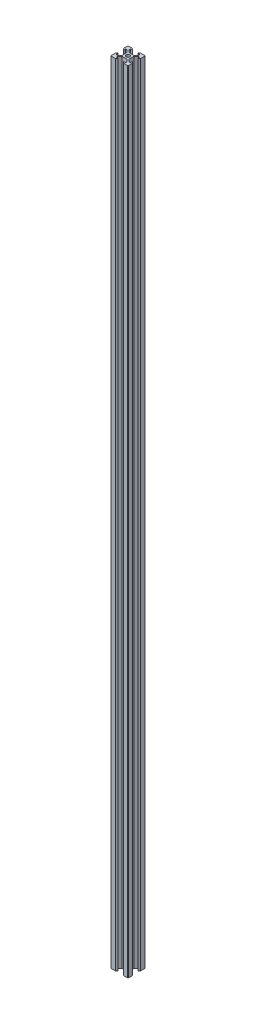
SolidWorks part; units mm, degrees
ref_plane "Front Plane" through (0, 0, 0) normal (0, 0, 1) x (1, 0, 0)
ref_plane "Top Plane" through (0, 0, 0) normal (0, 1, 0) x (1, 0, 0)
ref_plane "Right Plane" through (0, 0, 0) normal (1, 0, 0) x (0, 0, -1)
sketch "Sketch1" plane through (0, 0, 0) normal (1, 0, 0) x (0, 0, -1)
  line L0 (0, 0) -> (0, 914.4)
  dimension "D1" = 914.4
other "Vslot2020 2020(5)"
ref_plane "Plane5" through (0, 0, 0) normal (0, 1, 0) x (0, 0, 1)
sketch "Sketch2" plane through (0, 0, 0) normal (0, 1, 0) x (0, 0, 1)
  line L58 (13.9, 7.1491) -> (13.9, 12.8445)
  line L59 (13.9, 12.8445) -> (16.5585, 15.4922)
  line L60 (16.5585, 15.4922) -> (16.5507, 15.5)
  line L61 (16.5507, 15.5) -> (18.2, 15.5)
  line L62 (18.2, 15.5) -> (18.2, 13.12)
  line L63 (18.2, 13.12) -> (18.5344, 13.12)
  line L64 (18.5344, 13.12) -> (20, 14.58)
  line L65 (20, 14.58) -> (20, 19.5)
  line L66 (19.5, 20) -> (14.575, 20)
  line L67 (14.575, 20) -> (13.12, 18.545)
  line L68 (13.12, 18.545) -> (13.12, 18.2)
  line L69 (13.12, 18.2) -> (15.5, 18.2)
  line L70 (15.5, 18.2) -> (15.5, 16.555)
  line L71 (15.5, 16.555) -> (12.8341, 13.9)
  line L72 (12.8341, 13.9) -> (7.155, 13.9)
  line L73 (7.155, 13.9) -> (4.5, 16.555)
  line L74 (4.5, 16.555) -> (4.5, 18.2)
  line L75 (4.5, 18.2) -> (6.875, 18.2)
  line L76 (6.875, 18.2) -> (6.875, 18.545)
  line L77 (6.875, 18.545) -> (5.42, 20)
  line L78 (5.42, 20) -> (0.5, 20)
  line L79 (0, 19.5) -> (0, 14.58)
  line L80 (0, 14.58) -> (1.46, 13.12)
  line L81 (1.46, 13.12) -> (1.8, 13.12)
  line L82 (1.8, 13.12) -> (1.8, 15.5)
  line L83 (1.8, 15.5) -> (3.445, 15.5)
  line L84 (3.445, 15.5) -> (3.4393, 15.4943)
  line L85 (3.4393, 15.4943) -> (6.0943, 12.8393)
  line L86 (6.0943, 12.8393) -> (6.1, 12.845)
  line L87 (6.1, 12.845) -> (6.1, 7.1491)
  line L88 (6.1, 7.1491) -> (3.4393, 4.5)
  line L89 (3.4393, 4.5) -> (1.8, 4.5)
  line L90 (1.8, 4.5) -> (1.8, 6.88)
  line L91 (1.8, 6.88) -> (1.46, 6.88)
  line L92 (1.46, 6.88) -> (0, 5.42)
  line L93 (0, 5.42) -> (0, 0.5)
  line L94 (0.5, 0) -> (5.42, 0)
  line L95 (5.42, 0) -> (6.875, 1.455)
  line L96 (6.875, 1.455) -> (6.875, 1.8)
  line L97 (6.875, 1.8) -> (4.5, 1.8)
  line L98 (4.5, 1.8) -> (4.5, 3.4393)
  line L99 (4.5, 3.4393) -> (7.1583, 6.0861)
  line L100 (7.1583, 6.0861) -> (7.1445, 6.1)
  line L101 (7.1445, 6.1) -> (12.8546, 6.1)
  line L102 (12.8546, 6.1) -> (12.8412, 6.0865)
  line L103 (12.8412, 6.0865) -> (15.4997, 3.4375)
  line L104 (15.4997, 3.4375) -> (15.5, 3.4377)
  line L105 (15.5, 3.4377) -> (15.5, 1.8)
  line L106 (15.5, 1.8) -> (13.12, 1.8)
  line L107 (13.12, 1.8) -> (13.12, 1.455)
  line L108 (13.12, 1.455) -> (14.575, 0)
  line L109 (14.575, 0) -> (19.5, 0)
  line L110 (20, 0.5) -> (20, 5.42)
  line L111 (20, 5.42) -> (18.6069, 6.88)
  line L112 (18.6069, 6.88) -> (18.2, 6.88)
  line L113 (18.2, 6.88) -> (18.2, 4.5)
  line L114 (18.2, 4.5) -> (16.5585, 4.5)
  line L115 (16.5585, 4.5) -> (13.9, 7.1491)
  line L116 (13.9, 7.1491) -> (13.9, 12.8445)
  line L117 (13.9, 12.8445) -> (16.5585, 15.4922)
  line L118 (16.5585, 15.4922) -> (16.5507, 15.5)
  line L119 (16.5507, 15.5) -> (18.2, 15.5)
  line L120 (18.2, 15.5) -> (18.2, 13.12)
  line L121 (18.2, 13.12) -> (18.5344, 13.12)
  line L122 (18.5344, 13.12) -> (20, 14.58)
  line L123 (20, 14.58) -> (20, 19.5)
  line L124 (19.5, 20) -> (14.575, 20)
  line L125 (14.575, 20) -> (13.12, 18.545)
  line L126 (13.12, 18.545) -> (13.12, 18.2)
  line L127 (13.12, 18.2) -> (15.5, 18.2)
  line L128 (15.5, 18.2) -> (15.5, 16.555)
  line L129 (15.5, 16.555) -> (12.8341, 13.9)
  line L130 (12.8341, 13.9) -> (7.155, 13.9)
  line L131 (7.155, 13.9) -> (4.5, 16.555)
  line L132 (4.5, 16.555) -> (4.5, 18.2)
  line L133 (4.5, 18.2) -> (6.875, 18.2)
  line L134 (6.875, 18.2) -> (6.875, 18.545)
  line L135 (6.875, 18.545) -> (5.42, 20)
  line L136 (5.42, 20) -> (0.5, 20)
  line L137 (0, 19.5) -> (0, 14.58)
  line L138 (0, 14.58) -> (1.46, 13.12)
  line L139 (1.46, 13.12) -> (1.8, 13.12)
  line L140 (1.8, 13.12) -> (1.8, 15.5)
  line L141 (1.8, 15.5) -> (3.445, 15.5)
  line L142 (3.445, 15.5) -> (3.4393, 15.4943)
  line L143 (3.4393, 15.4943) -> (6.0943, 12.8393)
  line L144 (6.0943, 12.8393) -> (6.1, 12.845)
  line L145 (6.1, 12.845) -> (6.1, 7.1491)
  line L146 (6.1, 7.1491) -> (3.4393, 4.5)
  line L147 (3.4393, 4.5) -> (1.8, 4.5)
  line L148 (1.8, 4.5) -> (1.8, 6.88)
  line L149 (1.8, 6.88) -> (1.46, 6.88)
  line L150 (1.46, 6.88) -> (0, 5.42)
  line L151 (0, 5.42) -> (0, 0.5)
  line L152 (0.5, 0) -> (5.42, 0)
  line L153 (5.42, 0) -> (6.875, 1.455)
  line L154 (6.875, 1.455) -> (6.875, 1.8)
  line L155 (6.875, 1.8) -> (4.5, 1.8)
  line L156 (4.5, 1.8) -> (4.5, 3.4393)
  line L157 (4.5, 3.4393) -> (7.1583, 6.0861)
  line L158 (7.1583, 6.0861) -> (7.1445, 6.1)
  line L159 (7.1445, 6.1) -> (12.8546, 6.1)
  line L160 (12.8546, 6.1) -> (12.8412, 6.0865)
  line L161 (12.8412, 6.0865) -> (15.4997, 3.4375)
  line L162 (15.4997, 3.4375) -> (15.5, 3.4377)
  line L163 (15.5, 3.4377) -> (15.5, 1.8)
  line L164 (15.5, 1.8) -> (13.12, 1.8)
  line L165 (13.12, 1.8) -> (13.12, 1.455)
  line L166 (13.12, 1.455) -> (14.575, 0)
  line L167 (14.575, 0) -> (19.5, 0)
  line L168 (20, 0.5) -> (20, 5.42)
  line L169 (20, 5.42) -> (18.6069, 6.88)
  line L170 (18.6069, 6.88) -> (18.2, 6.88)
  line L171 (18.2, 6.88) -> (18.2, 4.5)
  line L172 (18.2, 4.5) -> (16.5585, 4.5)
  line L173 (16.5585, 4.5) -> (13.9, 7.1491)
  circle A0 centre (10, 10) radius 2.0746 construction
  circle A1 centre (10, 10) radius 2.0746
  arc A4 (20, 19.5) -> (19.5, 20) centre (19.5, 19.5) ccw
  arc A5 (0.5, 20) -> (0, 19.5) centre (0.5, 19.5) ccw
  arc A6 (0, 0.5) -> (0.5, 0) centre (0.5, 0.5) ccw
  arc A7 (19.5, 0) -> (20, 0.5) centre (19.5, 0.5) ccw
  arc A8 (20, 19.5) -> (19.5, 20) centre (19.5, 19.5) ccw
  arc A9 (0.5, 20) -> (0, 19.5) centre (0.5, 19.5) ccw
  arc A10 (0, 0.5) -> (0.5, 0) centre (0.5, 0.5) ccw
  arc A11 (19.5, 0) -> (20, 0.5) centre (19.5, 0.5) ccw
  point P16 (0, 0)
  dimension "D1" = 0
